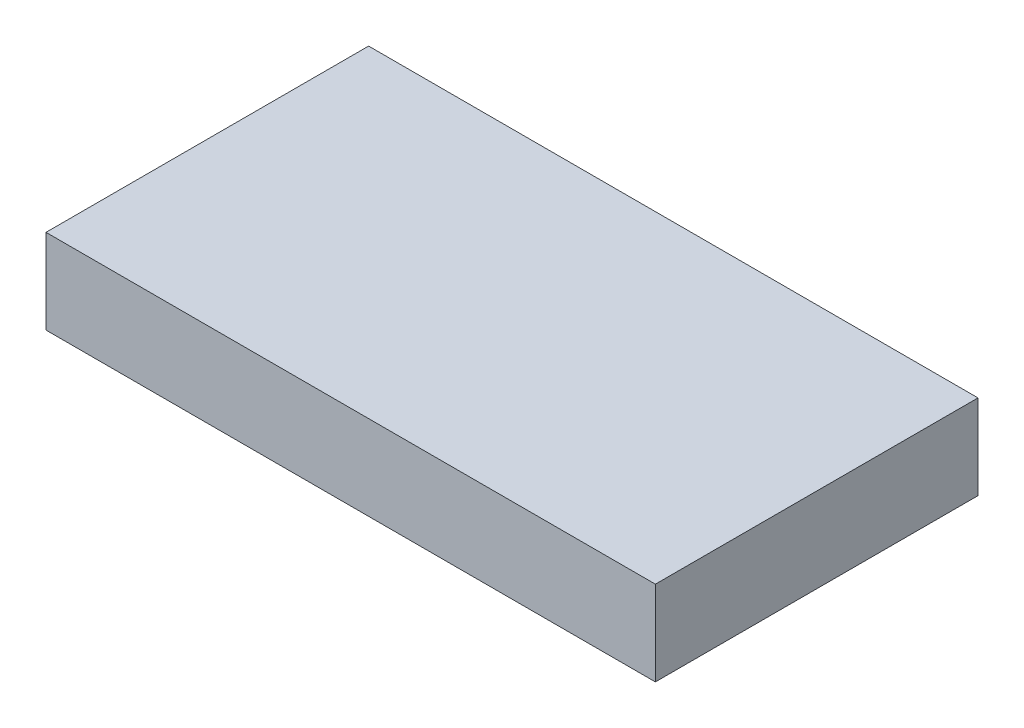
SolidWorks part; units mm, degrees
ref_plane "Front" through (0, 0, 0) normal (0, 0, 1) x (1, 0, 0)
ref_plane "Top" through (0, 0, 0) normal (0, 1, 0) x (1, 0, 0)
ref_plane "Right" through (0, 0, 0) normal (1, 0, 0) x (0, 0, -1)
sketch "Sketch1" plane through (0, 0, 0) normal (0, 1, 0) x (1, 0, 0)
  line L1 (-100.4574, 18.4233) -> (115.4426, 18.4233)
  line L2 (-100.4574, 18.4233) -> (-100.4574, -95.8767)
  line L3 (-100.4574, -95.8767) -> (115.4426, -95.8767)
  line L4 (115.4426, 18.4233) -> (115.4426, -95.8767)
  dimension "D1" = 215.9
  dimension "D2" = 114.3
extrude "Boss-Extrude1" add sketch "Sketch1" along normal blind 30
